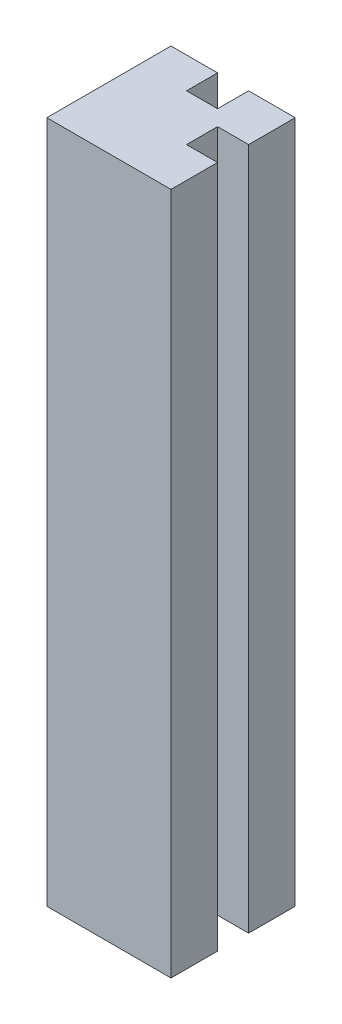
SolidWorks part; units mm, degrees
material "Kiefer"
ref_plane "Ebene vorne" through (0, 0, 0) normal (0, 0, 1) x (1, 0, 0)
ref_plane "Ebene oben" through (0, 0, 0) normal (0, 1, 0) x (1, 0, 0)
ref_plane "Ebene rechts" through (0, 0, 0) normal (1, 0, 0) x (0, 0, -1)
sketch "Skizze1" plane through (0, 0, 0) normal (0, 1, 0) x (1, 0, 0)
  line L1 (-10, 10) -> (10, 10)
  line L2 (-10, 10) -> (-10, -10)
  line L3 (-10, -10) -> (10, -10)
  line L4 (10, 10) -> (10, -10)
  line L5 (-10, 10) -> (10, -10) construction
  line L6 (-10, -10) -> (10, 10) construction
  point P0 (0, 0)
  dimension "D1" = 20
  dimension "D2" = 20
extrude "Aufsatz-Linear austragen1" add sketch "Skizze1" along normal blind 110
sketch "Skizze2" plane through (0, 110, 0) normal (0, 1, 0) x (1, 0, 0)
  line L0 (10, 10) -> (-10, 10) construction
  line L1 (-2.5, 15) -> (2.5, 15)
  line L2 (-2.5, 15) -> (-2.5, 5)
  line L3 (-2.5, 5) -> (2.5, 5)
  line L4 (2.5, 15) -> (2.5, 5)
  line L5 (-2.5, 15) -> (2.5, 5) construction
  line L6 (-2.5, 5) -> (2.5, 15) construction
  line L7 (10, -10) -> (10, 10) construction
  line L8 (5, 2.5) -> (15, 2.5)
  line L9 (5, 2.5) -> (5, -2.5)
  line L10 (5, -2.5) -> (15, -2.5)
  line L11 (15, 2.5) -> (15, -2.5)
  line L12 (5, 2.5) -> (15, -2.5) construction
  line L13 (5, -2.5) -> (15, 2.5) construction
  point P0 (0, 10)
  point P7 (10, 0)
  dimension "D1" = 5
  dimension "D2" = 5
  dimension "D3" = 5
  dimension "D4" = 5
extrude "Schnitt-Linear austragen1" cut sketch "Skizze2" against normal through all
